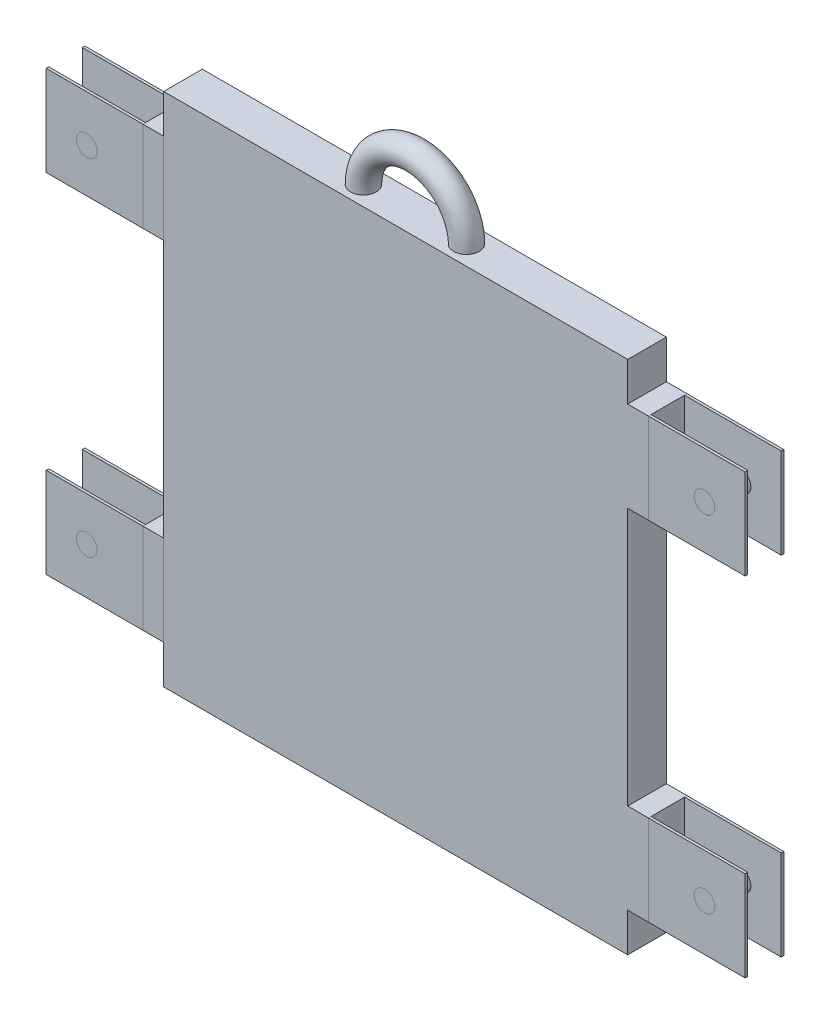
SolidWorks part; units mm, degrees
ref_plane "Front Plane" through (0, 0, 0) normal (0, 0, 1) x (1, 0, 0)
ref_plane "Top Plane" through (0, 0, 0) normal (0, 1, 0) x (1, 0, 0)
ref_plane "Right Plane" through (0, 0, 0) normal (1, 0, 0) x (0, 0, -1)
sketch "Sketch1" plane through (0, 0, 0) normal (0, 0, 1) x (1, 0, 0)
  line L1 (-90, 100) -> (90, 100)
  line L2 (-90, 100) -> (-90, -100)
  line L3 (-90, -100) -> (90, -100)
  line L4 (90, 100) -> (90, -100)
  line L5 (-90, 100) -> (90, -100) construction
  line L6 (-90, -100) -> (90, 100) construction
  point P0 (0, 0)
  dimension "D1" = 180
  dimension "D2" = 200
extrude "Boss-Extrude1" add sketch "Sketch1" along normal blind 15
sketch "Sketch3" plane through (-90, 0, 0) normal (-1, 0, 0) x (0, 0, 1)
  line L0 (0, 100) -> (0, -100) construction
  line L1 (0, 85) -> (15, 85)
  line L2 (0, 85) -> (0, 50)
  line L3 (0, 50) -> (15, 50)
  line L4 (15, 85) -> (15, 50)
  line L5 (15, 100) -> (15, -100) construction
  line L6 (8.25, 0) -> (-8.25, 0) construction
  line L7 (0, -50) -> (15, -50)
  line L8 (15, -85) -> (15, -50)
  line L9 (0, -85) -> (15, -85)
  line L10 (0, -85) -> (0, -50)
  dimension "D1" = 35
  dimension "D2" = 50
extrude "Boss-Extrude2" add sketch "Sketch3" along normal blind 8.04 separate body
sketch "Sketch4" plane through (-98.04, 0, 0) normal (-1, 0, 0) x (0, 0, 1)
  line L0 (0, 50) -> (15, 50) construction
  line L1 (0, 85) -> (1, 85)
  line L2 (0, 85) -> (0, 50)
  line L3 (0, 50) -> (1, 50)
  line L4 (1, 85) -> (1, 50)
  line L5 (15, 85) -> (0, 85) construction
  line L6 (15, 50) -> (14, 50)
  line L7 (15, 50) -> (15, 85)
  line L8 (15, 85) -> (14, 85)
  line L9 (14, 50) -> (14, 85)
  line L10 (8.25, 0) -> (-8.25, 0) construction
  line L11 (15, -85) -> (14, -85)
  line L12 (14, -50) -> (14, -85)
  line L13 (15, -50) -> (14, -50)
  line L14 (15, -50) -> (15, -85)
  line L15 (0, -50) -> (1, -50)
  line L16 (1, -85) -> (1, -50)
  line L17 (0, -85) -> (1, -85)
  line L18 (0, -85) -> (0, -50)
  dimension "D1" = 1
  dimension "D2" = 1
extrude "Boss-Extrude3" add sketch "Sketch4" along normal blind 37.5 separate body
mirror "Mirror6" about plane through (0, 0, 0) normal (1, 0, 0) of "Boss-Extrude3", "Boss-Extrude2"
sketch "Sketch5" plane through (98.04, 0, 0) normal (1, 0, 0) x (0, 0, -1)
  line L0 (0, 50) -> (-15, 50) construction
  line L1 (-15, 85) -> (-14, 85)
  line L2 (-15, 85) -> (-15, 50)
  line L3 (-15, 50) -> (-14, 50)
  line L4 (-14, 85) -> (-14, 50)
  line L5 (8.25, 0) -> (-8.25, 0) construction
  line L6 (0, 85) -> (-1, 85)
  line L7 (0, 85) -> (0, 50)
  line L8 (0, 50) -> (-1, 50)
  line L9 (-1, 85) -> (-1, 50)
  line L10 (0, -50) -> (-1, -50)
  line L11 (-1, -85) -> (-1, -50)
  line L12 (0, -85) -> (-1, -85)
  line L13 (0, -85) -> (0, -50)
  line L14 (-15, -50) -> (-14, -50)
  line L15 (-14, -85) -> (-14, -50)
  line L16 (-15, -85) -> (-14, -85)
  line L17 (-15, -85) -> (-15, -50)
  dimension "D1" = 1
  dimension "D2" = 1
extrude "Boss-Extrude4" add sketch "Sketch5" along normal blind 37.5 separate body
sketch "Sketch6" plane through (0, 0, 15) normal (0, 0, 1) x (1, 0, 0)
  line L0 (0, 116.6404) -> (0, -122.9619) construction
  line L1 (-178.8303, 0) -> (231.5084, 0) construction
  line L3 (-98.04, -85) -> (-98.04, -50) construction
  line L4 (-135.54, -50) -> (-98.04, -50) construction
  circle A1 centre (-119.79, -67) radius 4
  circle A2 centre (119.79, -67) radius 4
  circle A4 centre (119.79, 67) radius 4
  circle A5 centre (-119.79, 67) radius 4
  dimension "D1" = 8
  dimension "D2" = 21.75
  dimension "D3" = 17
extrude "Cut-Extrude1" cut sketch "Sketch6" against normal blind 40
sketch "Sketch7" plane through (0, 0, 15) normal (0, 0, 1) x (1, 0, 0)
  line L0 (0, 109.5624) -> (0, -113.8366) construction
  line L1 (8.25, 0) -> (-8.25, 0) construction
  circle A0 centre (-119.79, 67) radius 4
  circle A1 centre (119.79, 67) radius 4
  circle A2 centre (119.79, -67) radius 4
  circle A3 centre (-119.79, -67) radius 4
  dimension "D1" = 8
extrude "Boss-Extrude5" add sketch "Sketch7" against normal up to vertex (15 mm away) separate body
sketch "Sketch8" plane through (0, 100, 0) normal (0, 1, 0) x (1, 0, 0)
  line L0 (0, 60.6524) -> (0, -110.1322) construction
  line L1 (90, -15) -> (-90, -15) construction
  circle A0 centre (-20, -7.5) radius 5
  dimension "D2" = 10
  dimension "D1" = 20
  dimension "D3" = 7.5
revolve "Revolve1" add sketch "Sketch8" angle 360 about L0
